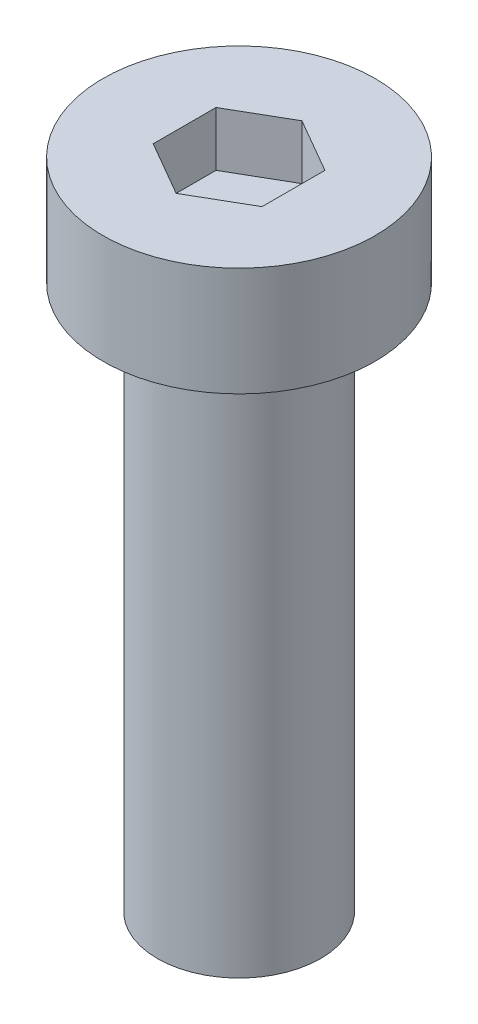
SolidWorks part; units mm, degrees
ref_plane "Front Plane" through (0, 0, 0) normal (0, 0, 1) x (1, 0, 0)
ref_plane "Top Plane" through (0, 0, 0) normal (0, 1, 0) x (1, 0, 0)
ref_plane "Right Plane" through (0, 0, 0) normal (1, 0, 0) x (0, 0, -1)
sketch "Sketch1" plane through (0, 0, 0) normal (0, 0, 1) x (1, 0, 0)
  line L0 (0, 0) -> (0, 24)
  line L1 (0, 24) -> (5, 24)
  line L2 (5, 24) -> (5, 20)
  line L3 (5, 20) -> (3, 20)
  line L4 (3, 20) -> (3, 0)
  line L5 (3, 0) -> (0, 0)
  dimension "D1" = 3
  dimension "D2" = 5
  dimension "D3" = 4
  dimension "D4" = 20
revolve "Revolve1" add sketch "Sketch1" angle 360 about L0
sketch "Sketch2" plane through (0, 24, 0) normal (0, 1, 0) x (1, 0, 0)
  line L1 (0, -2.3094) -> (2, -1.1547)
  line L2 (2, -1.1547) -> (2, 1.1547)
  line L3 (2, 1.1547) -> (0, 2.3094)
  line L4 (0, 2.3094) -> (-2, 1.1547)
  line L5 (-2, 1.1547) -> (-2, -1.1547)
  line L6 (-2, -1.1547) -> (0, -2.3094)
  circle A0 centre (0, 0) radius 2 construction
  dimension "D1" = 4
extrude "Cut-Extrude1" cut sketch "Sketch2" against normal blind 2
